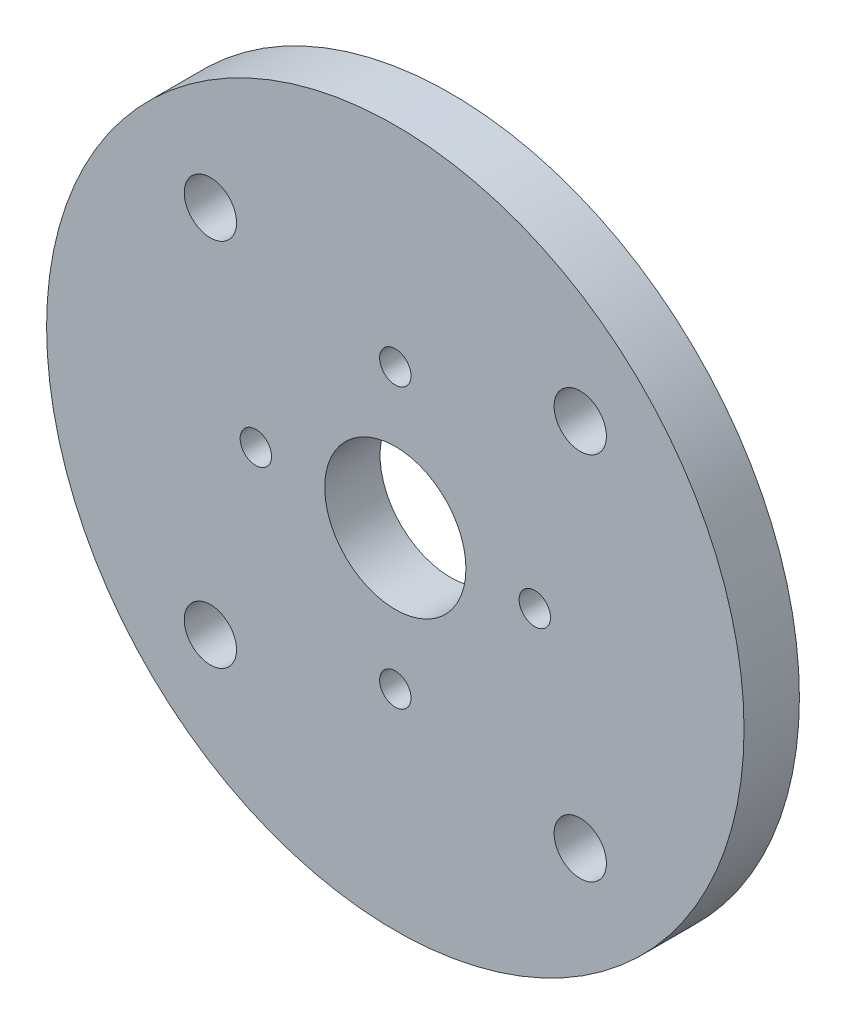
SolidWorks part; units mm, degrees
material "Acrylique (impact moyen-haut)"
ref_plane "Plan de face" through (0, 0, 0) normal (0, 0, 1) x (1, 0, 0)
ref_plane "Plan de dessus" through (0, 0, 0) normal (0, 1, 0) x (1, 0, 0)
ref_plane "Plan de droite" through (0, 0, 0) normal (1, 0, 0) x (0, 0, -1)
sketch "Esquisse1" plane through (0, 0, 0) normal (0, 0, 1) x (1, 0, 0)
  circle A0 centre (0, 0) radius 20
  dimension "D1" = 40
extrude "Boss.-Extru.1" add sketch "Esquisse1" along normal blind 3.175
sketch "Esquisse2" plane through (0, 0, 3.175) normal (0, 0, 1) x (1, 0, 0)
  line L0 (0, 0) -> (0, 8) construction
  line L1 (-8, 0) -> (0, 0) construction
  circle A0 centre (0, 0) radius 4.05
  circle A1 centre (0, 0) radius 8 construction
  circle A2 centre (0, 8) radius 0.9
  circle A3 centre (8, 0) radius 0.9
  circle A4 centre (0, -8) radius 0.9
  circle A5 centre (-8, 0) radius 0.9
  point P15 (0, 0)
  dimension "D1" = 8.1
  dimension "D2" = 16
  dimension "D3" = 1.8
  dimension "D4" = 4
extrude "Enlèv. mat.-Extru.1" cut sketch "Esquisse2" against normal through all
sketch "Esquisse3" plane through (0, 0, 3.175) normal (0, 0, 1) x (1, 0, 0)
  line L0 (0, 0) -> (10.6066, 10.6066) construction
  line L1 (0, 0) -> (0, 15) construction
  circle A0 centre (0, 0) radius 15 construction
  circle A1 centre (10.6066, 10.6066) radius 1.5
  circle A2 centre (10.6066, -10.6066) radius 1.5
  circle A3 centre (-10.6066, -10.6066) radius 1.5
  circle A4 centre (-10.6066, 10.6066) radius 1.5
  point P15 (0, 0)
  dimension "D2" = 3
  dimension "D3" = 30
  dimension "D1" = 45
  dimension "D4" = 4
extrude "Enlèv. mat.-Extru.2" cut sketch "Esquisse3" against normal through all and the other way through all
